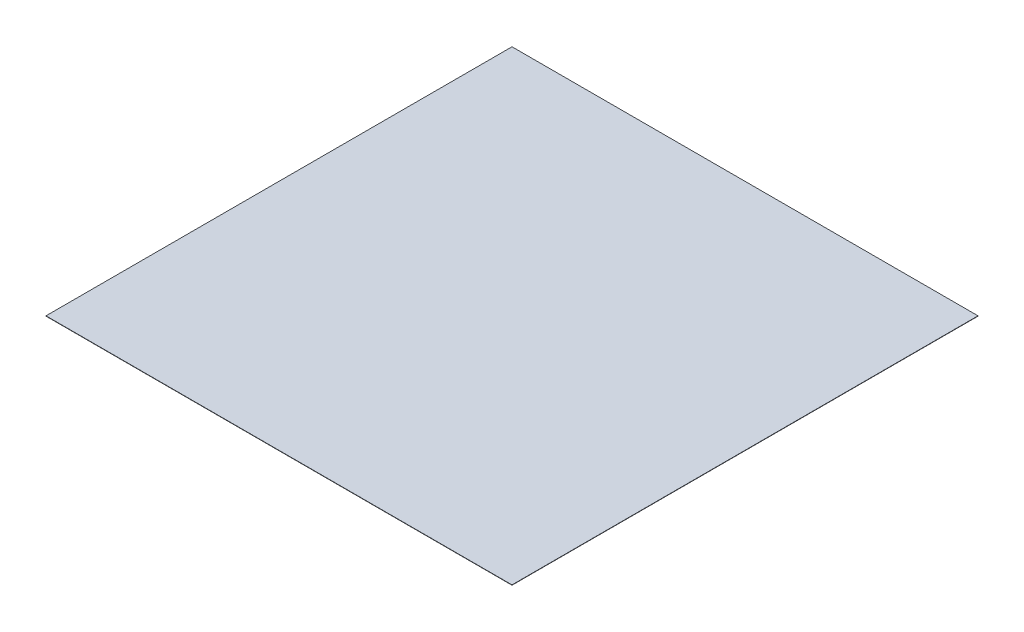
SolidWorks part; units mm, degrees
ref_plane "Front Plane" through (0, 0, 0) normal (0, 0, 1) x (1, 0, 0)
ref_plane "Top Plane" through (0, 0, 0) normal (0, 1, 0) x (1, 0, 0)
ref_plane "Right Plane" through (0, 0, 0) normal (1, 0, 0) x (0, 0, -1)
sketch "Sketch1" plane through (0, 0, 0) normal (0, 1, 0) x (1, 0, 0)
  line L1 (-47.625, -47.625) -> (47.625, -47.625)
  line L2 (-47.625, -47.625) -> (-47.625, 47.625)
  line L3 (-47.625, 47.625) -> (47.625, 47.625)
  line L4 (47.625, -47.625) -> (47.625, 47.625)
  line L5 (-47.625, -47.625) -> (47.625, 47.625) construction
  line L6 (-47.625, 47.625) -> (47.625, -47.625) construction
  point P0 (0, 0)
  dimension "D1" = 95.25
  dimension "D2" = 95.25
extrude "Boss-Extrude1" add sketch "Sketch1" along normal blind 0.065
